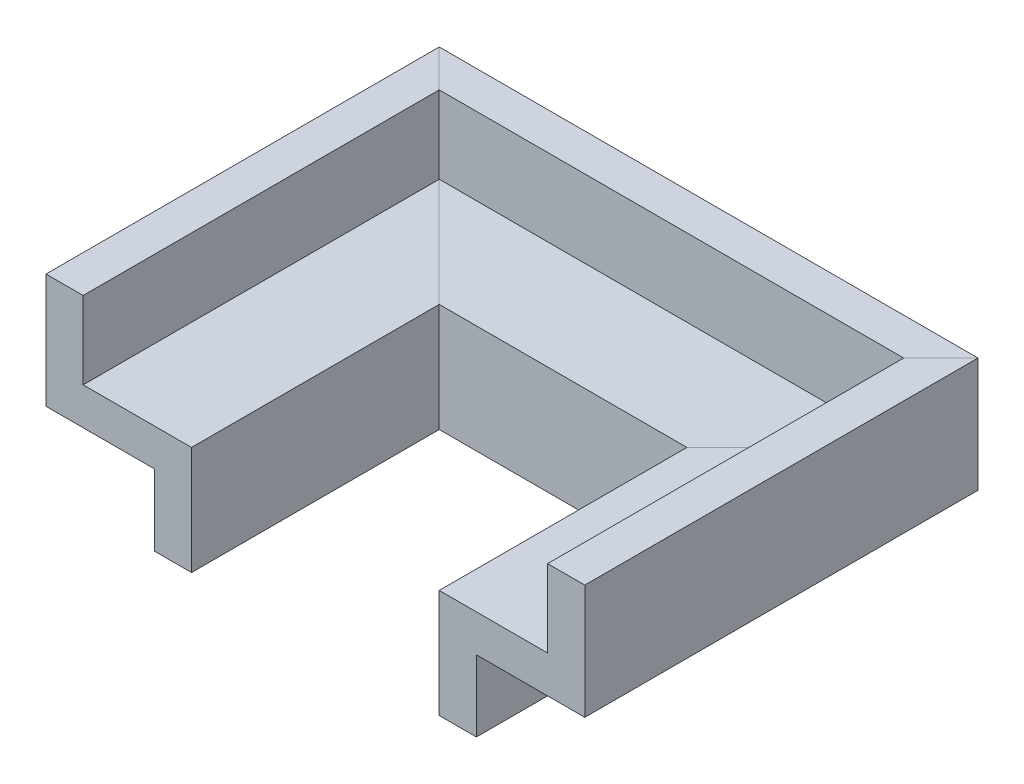
SolidWorks part; units mm, degrees
ref_plane "Front Plane" through (0, 0, 0) normal (0, 0, 1) x (1, 0, 0)
ref_plane "Top Plane" through (0, 0, 0) normal (0, 1, 0) x (1, 0, 0)
ref_plane "Right Plane" through (0, 0, 0) normal (1, 0, 0) x (0, 0, -1)
sketch "Sketch1" plane through (0, 0, 0) normal (0, 0, 1) x (1, 0, 0)
  line L0 (0, 0) -> (0, 35)
  line L1 (0, 35) -> (-35, 35)
  line L2 (-35, 35) -> (-35, 60)
  line L3 (-35, 60) -> (-47, 60)
  line L4 (-47, 60) -> (-47, 23)
  line L5 (-47, 23) -> (-12, 23)
  line L6 (-12, 23) -> (-12, 0)
  line L7 (-12, 0) -> (0, 0)
  point P9 (-6, 0)
  dimension "D1" = 12
  dimension "D2" = 12
  dimension "D3" = 12
  dimension "D4" = 35
  dimension "D5" = 47
  dimension "D6" = 60
sketch "Sketch2" plane through (0, 0, 0) normal (0, 1, 0) x (1, 0, 0)
  line L0 (0, 0) -> (0, 80)
  line L1 (0, 80) -> (80, 80)
  line L2 (80, 80) -> (80, 0)
  dimension "D1" = 80
  dimension "D2" = 80
  dimension "D3" = 80
sweep "Sweep1" add profiles "Sketch1" path "Sketch2"
